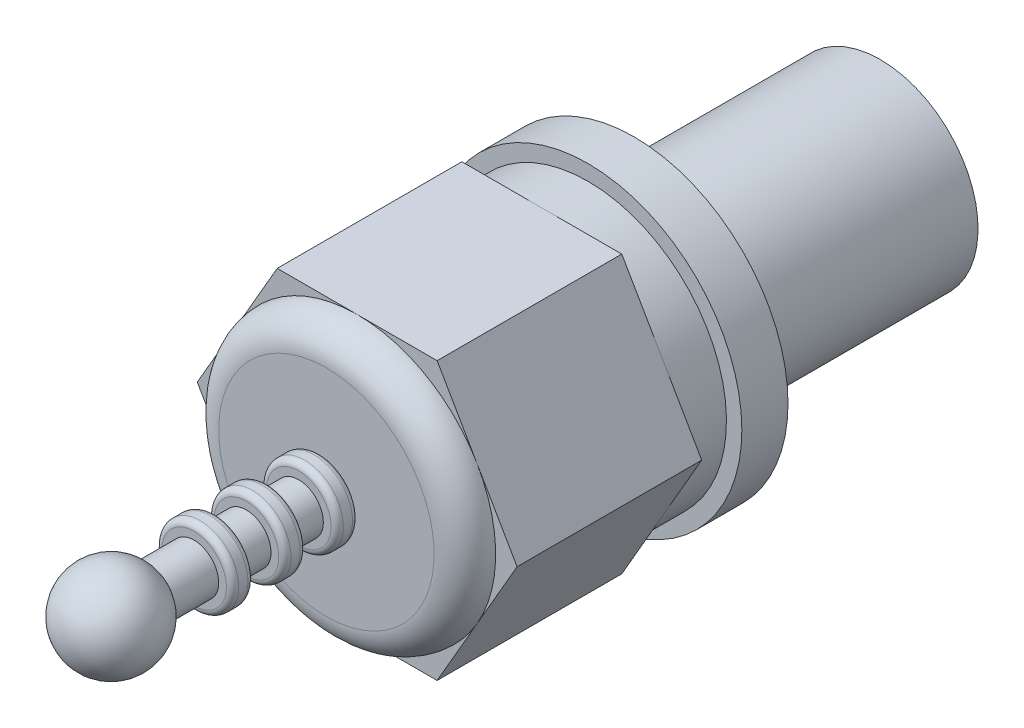
SolidWorks part; units mm, degrees
material "AISI Type 316L stainless steel"
ref_plane "Front Plane" through (0, 0, 0) normal (0, 0, 1) x (1, 0, 0)
ref_plane "Top Plane" through (0, 0, 0) normal (0, 1, 0) x (1, 0, 0)
ref_plane "Right Plane" through (0, 0, 0) normal (1, 0, 0) x (0, 0, -1)
sketch "Sketch1" plane through (0, 0, 0) normal (1, 0, 0) x (0, 0, -1)
  line L0 (17, 0) -> (-13.6485, 0) construction
  line L1 (17, 0) -> (17, 3.175)
  line L2 (17, 3.175) -> (9, 3.175)
  line L3 (9, 3.175) -> (9, 5)
  line L4 (7.5, 4.5) -> (0, 4.5)
  line L5 (-1, 3.5) -> (-1, 0.8)
  line L6 (-1, 0.8) -> (-1.2, 0.8)
  line L7 (7.5, 4.5) -> (7.5, 5)
  line L8 (7.5, 5) -> (9, 5)
  line L9 (-5.3, 0.8) -> (-6.7311, 0.8)
  line L10 (-3.6, 0.8) -> (-4.6, 0.8)
  line L11 (-5.3, 0.8) -> (-5.3, 1.05)
  line L12 (-5.1, 1.25) -> (-4.8, 1.25)
  line L13 (-4.6, 0.8) -> (-4.6, 1.05)
  line L14 (-1.9, 0.8) -> (-2.9, 0.8)
  line L15 (-3.6, 0.8) -> (-3.6, 1.05)
  line L16 (-3.4, 1.25) -> (-3.1, 1.25)
  line L17 (-2.9, 0.8) -> (-2.9, 1.05)
  line L19 (-1.9, 0.8) -> (-1.9, 1.05)
  line L20 (-1.7, 1.25) -> (-1.4, 1.25)
  line L21 (-1.2, 0.8) -> (-1.2, 1.05)
  line L22 (-9.5, 0) -> (17, 0)
  arc A0 (-6.7311, 0.8) -> (-9.5, 0) centre (-8, 0) ccw
  arc A1 (0, 4.5) -> (-1, 3.5) centre (0, 3.5) ccw
  arc A2 (-1.4, 1.25) -> (-1.2, 1.05) centre (-1.4, 1.05) cw
  arc A3 (-1.9, 1.05) -> (-1.7, 1.25) centre (-1.7, 1.05) cw
  arc A4 (-3.1, 1.25) -> (-2.9, 1.05) centre (-3.1, 1.05) cw
  arc A5 (-3.6, 1.05) -> (-3.4, 1.25) centre (-3.4, 1.05) cw
  arc A6 (-4.8, 1.25) -> (-4.6, 1.05) centre (-4.8, 1.05) cw
  arc A7 (-5.3, 1.05) -> (-5.1, 1.25) centre (-5.1, 1.05) cw
  point P12 (-1, 4.5)
  point P39 (-4.6, 1.25)
  dimension "D5" = 3
  dimension "D8" = 1
  dimension "D15" = 0.2
  dimension "D1" = 6.35
  dimension "D2" = 9
  dimension "D3" = 1.6
  dimension "D4" = 8
  dimension "D6" = 10
  dimension "D7" = 7
  dimension "D9" = 1.5
  dimension "D10" = 10
  dimension "D11" = 0.7
  dimension "D12" = 0.2
  dimension "D13" = 1
  dimension "D14" = 2.5
revolve "Revolve1" add sketch "Sketch1" angle 360 about L0
sketch "Sketch2" plane through (0, 0, 0) normal (0, 0, 1) x (1, 0, 0)
  line L1 (-2.5981, 4.5) -> (-5.1962, 0)
  line L2 (-5.1962, 0) -> (-2.5981, -4.5)
  line L3 (-2.5981, -4.5) -> (2.5981, -4.5)
  line L4 (2.5981, -4.5) -> (5.1962, 0)
  line L5 (5.1962, 0) -> (2.5981, 4.5)
  line L6 (2.5981, 4.5) -> (-2.5981, 4.5)
  circle A0 centre (0, 0) radius 4.5 construction
  circle A1 centre (0, 0) radius 4.5 construction
extrude "Boss-Extrude1" add sketch "Sketch2" against normal blind 6
